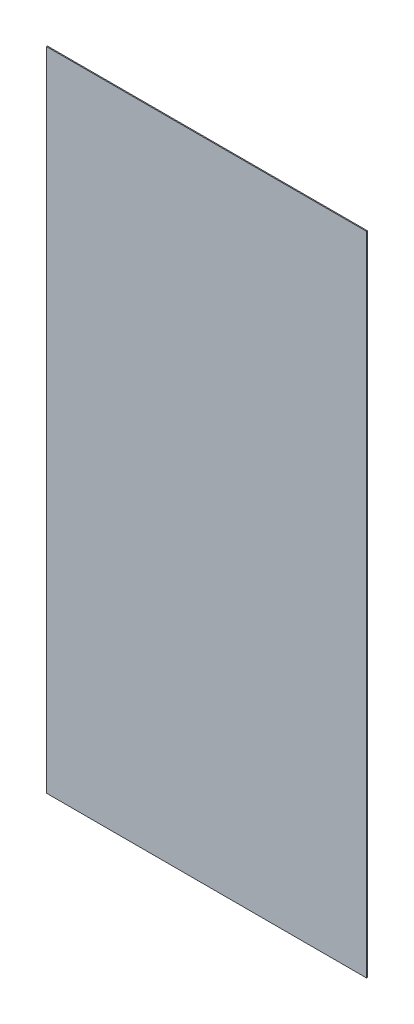
SolidWorks part; units mm, degrees
ref_plane "Alzado" through (0, 0, 0) normal (0, 0, 1) x (1, 0, 0)
ref_plane "Planta" through (0, 0, 0) normal (0, 1, 0) x (1, 0, 0)
ref_plane "Vista lateral" through (0, 0, 0) normal (1, 0, 0) x (0, 0, -1)
sketch "Croquis1" plane through (0, 0, 0) normal (0, 0, 1) x (1, 0, 0)
  line L0 (10, 10) -> (10, 1990)
  line L1 (0, 0) -> (1000, 0)
  line L2 (0, 0) -> (0, 2000)
  line L3 (0, 2000) -> (1000, 2000)
  line L4 (1000, 0) -> (1000, 2000)
  line L5 (10, 1990) -> (990, 1990)
  line L6 (990, 10) -> (990, 1990)
  line L7 (10, 10) -> (990, 10)
  line L8 (30, 1970) -> (970, 1970)
  line L9 (970, 30) -> (970, 1970)
  line L10 (30, 30) -> (970, 30)
  line L11 (30, 30) -> (30, 1970)
  dimension "D1" = 10
  dimension "D2" = 30
extrude "Saliente-Extruir1" add sketch "Croquis1" along normal blind 3 contours L11 L10 L9 L8 | L0 L7 L6 L5 L10 L11 L8 L9
